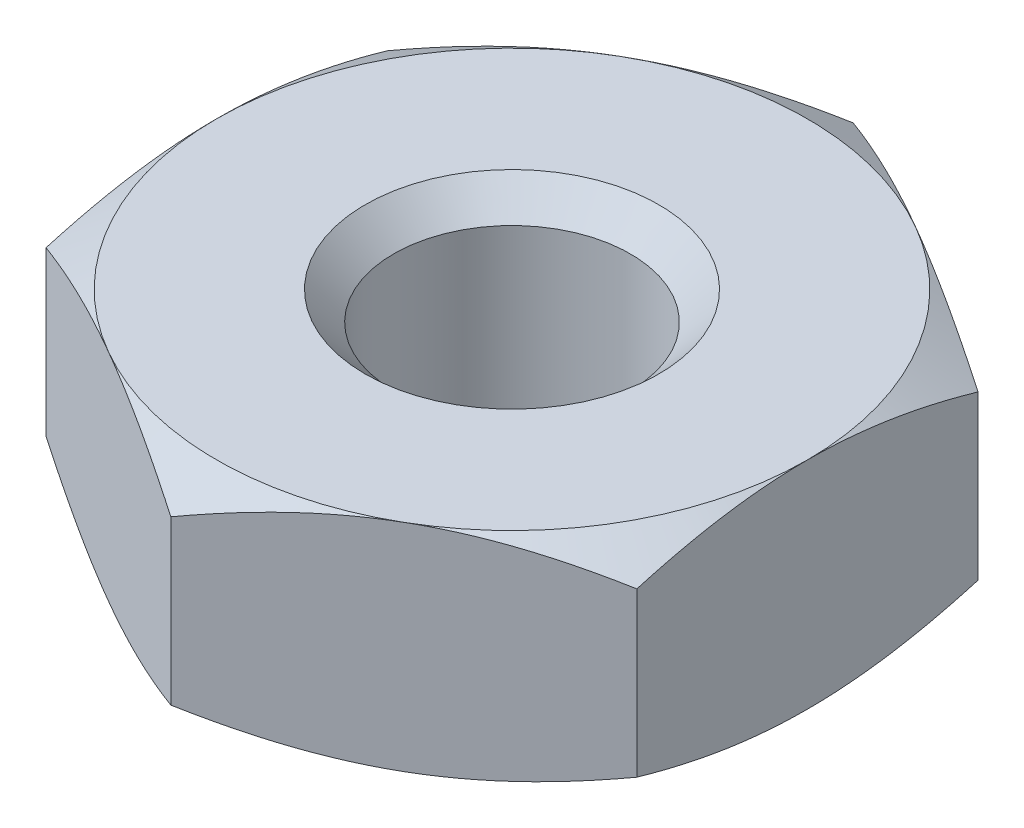
SolidWorks part; units mm, degrees
material "1023 Carbon Steel Sheet (SS)"
ref_plane "Front Plane" through (0, 0, 0) normal (0, 0, 1) x (1, 0, 0)
ref_plane "Top Plane" through (0, 0, 0) normal (0, 1, 0) x (1, 0, 0)
ref_plane "Right Plane" through (0, 0, 0) normal (1, 0, 0) x (0, 0, -1)
sketch "Sketch1" plane through (0, 0, 0) normal (0, 1, 0) x (1, 0, 0)
  line L1 (3.9624, -2.2877) -> (3.9624, 2.2877)
  line L2 (3.9624, 2.2877) -> (0, 4.5754)
  line L3 (0, 4.5754) -> (-3.9624, 2.2877)
  line L4 (-3.9624, 2.2877) -> (-3.9624, -2.2877)
  line L5 (-3.9624, -2.2877) -> (0, -4.5754)
  line L6 (0, -4.5754) -> (3.9624, -2.2877)
  circle A0 centre (0, 0) radius 3.9624 construction
  dimension "D1" = 7.9248
extrude "Boss-Extrude1" add sketch "Sketch1" along normal mid plane 2.8956
sketch "Sketch2" plane through (0, 1.4478, 0) normal (0, 1, 0) x (1, 0, 0)
  circle A0 centre (0, 0) radius 1.5875
  dimension "D1" = 3.175
extrude "Cut-Extrude1" cut sketch "Sketch2" against normal through all
sketch "Sketch3" plane through (0, 0, 0) normal (1, 0, 0) x (0, 0, -1)
  line L0 (0, 0) -> (0, -1.4478) construction
  line L1 (-2.2877, -1.4478) -> (2.2877, -1.4478) construction
  line L2 (-4.5754, -1.4478) -> (-4.5754, -1.0939)
  line L3 (-4.5754, 1.4478) -> (-4.5754, -1.4478) construction
  line L4 (-4.5754, -1.0939) -> (-3.9624, -1.4478)
  line L5 (-4.5754, -1.4478) -> (-2.2877, -1.4478) construction
  line L6 (-3.9624, -1.4478) -> (-4.5754, -1.4478)
  dimension "D1" = 30
  dimension "D2" = 7.9248
revolve "Cut-Revolve1" cut sketch "Sketch3" angle 360 about L0
mirror "Mirror1" about plane through (0, 0, 0) normal (0, 1, 0) of "Cut-Revolve1"
chamfer "Chamfer1" distance 0.381 angle 45 2 edges at (0, 1.4478, 1.5875) (0, -1.4478, 1.5875)
